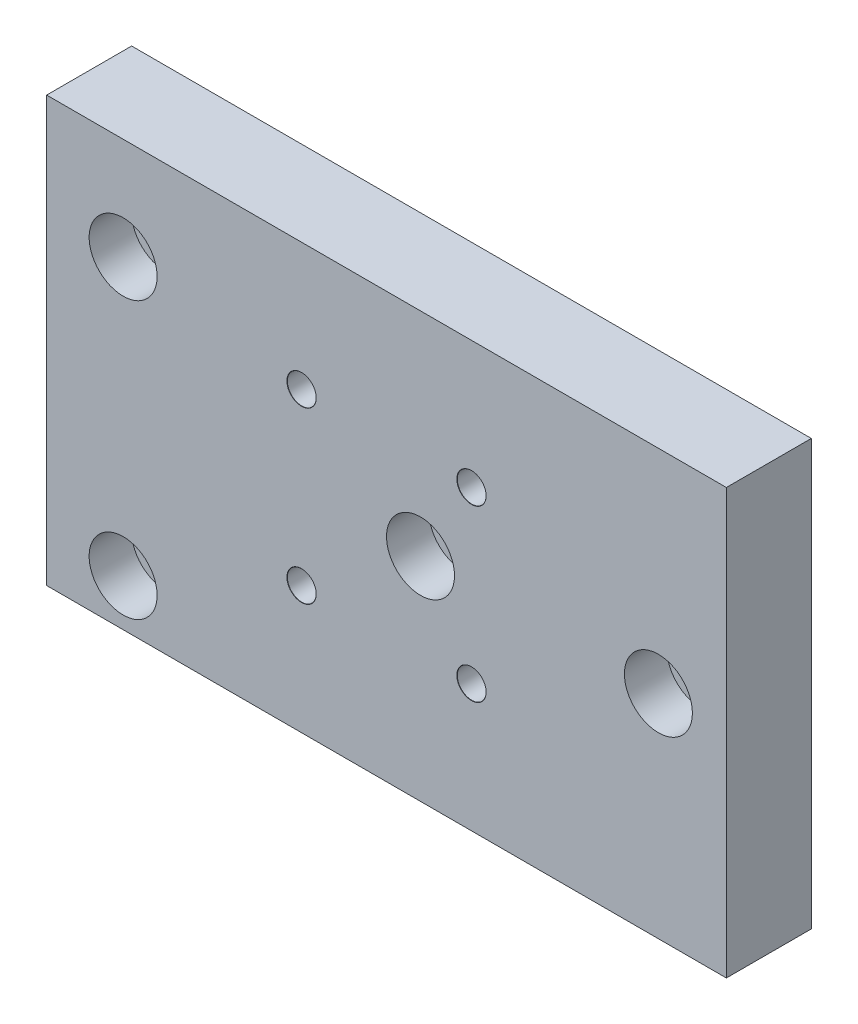
SolidWorks part; units mm, degrees
ref_plane "前视基准面" through (0, 0, 0) normal (0, 0, 1) x (1, 0, 0)
ref_plane "上视基准面" through (0, 0, 0) normal (0, 1, 0) x (1, 0, 0)
ref_plane "右视基准面" through (0, 0, 0) normal (1, 0, 0) x (0, 0, -1)
other "Configuration Table"
sketch "草图1" plane through (0, 0, 0) normal (0, 0, 1) x (1, 0, 0)
  line L1 (-40, 25) -> (40, 25)
  line L2 (-40, 25) -> (-40, -25)
  line L3 (-40, -25) -> (40, -25)
  line L4 (40, 25) -> (40, -25)
  line L5 (-40, 25) -> (40, -25) construction
  line L6 (-40, -25) -> (40, 25) construction
  point P0 (0, 0)
  dimension "D1" = 80
  dimension "D2" = 50
extrude "凸台-拉伸1" add sketch "草图1" along normal blind 10
sketch "草图5" plane through (0, 0, 0) normal (0, 0, -1) x (-1, 0, 0)
  circle A0 centre (-32, 0) radius 1.75
  circle A1 centre (-4, 0) radius 1.75
  circle A2 centre (31, 13) radius 1.75
  circle A3 centre (31, -19.5) radius 1.75
  dimension "D1" = 28
  dimension "D2" = 35
  dimension "D3" = 13
  dimension "D4" = 3.5
  dimension "D6" = 19.5
  dimension "D5" = 4
extrude "切除-拉伸1" cut sketch "草图5" against normal through all
sketch "草图6" plane through (0, 0, 10) normal (0, 0, 1) x (1, 0, 0)
  circle A0 centre (-31, 13) radius 4
  circle A1 centre (4, 0) radius 4
  circle A2 centre (32, 0) radius 4
  circle A3 centre (-31, -19.5) radius 4
  dimension "D1" = 8
extrude "切除-拉伸2" cut sketch "草图6" against normal blind 5
sketch "草图7" plane through (0, 0, 10) normal (0, 0, 1) x (1, 0, 0)
  line L1 (10, -10) -> (-10, -10)
  line L2 (10, -10) -> (10, 10)
  line L3 (10, 10) -> (-10, 10)
  line L4 (-10, -10) -> (-10, 10)
  point P1 (0, 0)
  point P6 (20.3359, 5.0543)
  point P7 (0, 0)
  point P8 (20.3359, -14.9457)
  point P9 (11.5341, 10.7565)
  dimension "D1" = 20
  dimension "D2" = 20
  dimension "D3" = 10
  dimension "D4" = 10
hole_wizard "M3 间隙孔1" positions "草图8" profile "草图9" hole size "M3" standard "GB" end condition through all
sketch "草图8" plane through (0, 0, 10) normal (0, 0, 1) x (1, 0, 0)
  point P0 (-10, 10)
  point P3 (10, 10)
  point P6 (10, -10)
  point P9 (-10, -10)
sketch "草图9" plane through (-10, 10, 10) normal (1, 0, 0) x (0, -1, 0)
  line L0 (0, 0) -> (0, 10)
  line L1 (0, 10) -> (1.7, 10)
  line L2 (1.7, 10) -> (1.7, 0.025)
  line L3 (1.7, 0.025) -> (1.725, 0)
  line L5 (1.725, 0) -> (0, 0)
  line L6 (-1.7, 0.025) -> (-1.725, 0) construction
  line L11 (0, -6.35) -> (0, 107.95) construction
  dimension "通孔孔直径" = 3.4
  dimension "通孔孔深度" = 10
  dimension "近端锥形沉头孔直径" = 3.45
  dimension "近端锥形沉头孔角度" = 90
